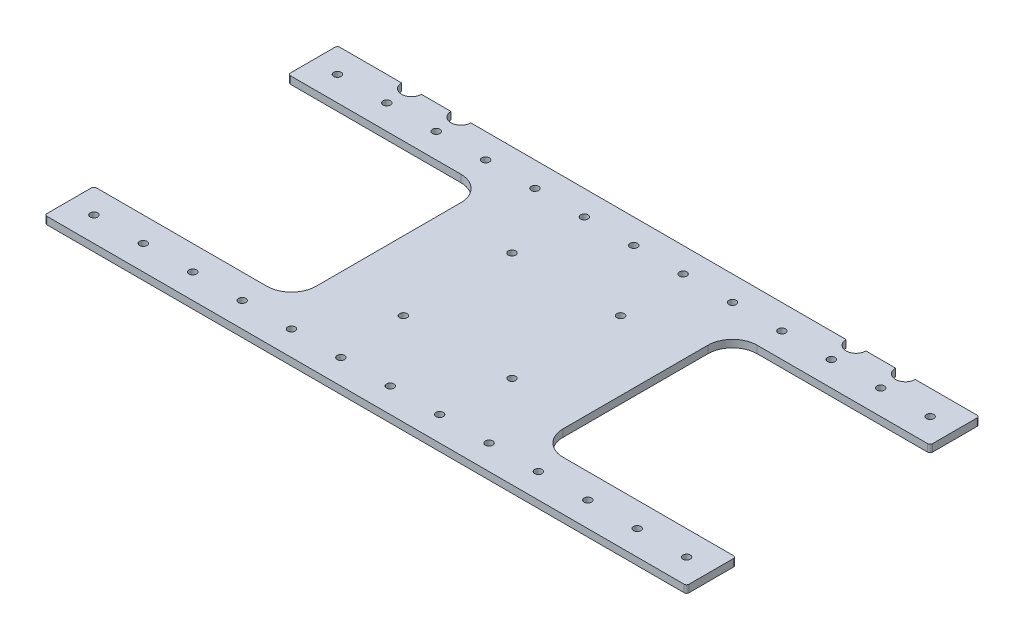
SolidWorks part; units mm, degrees
ref_plane "Front Plane" through (0, 0, 0) normal (0, 0, 1) x (1, 0, 0)
ref_plane "Top Plane" through (0, 0, 0) normal (0, 1, 0) x (1, 0, 0)
ref_plane "Right Plane" through (0, 0, 0) normal (1, 0, 0) x (0, 0, -1)
sketch "草图1" plane through (0, 0, 0) normal (0, 1, 0) x (1, 0, 0)
  line L0 (0, -1387.2) -> (0, -193.6) construction
  line L1 (-50, -193.6) -> (50, -193.6)
  line L2 (-50, -163.6) -> (-50, -105)
  line L3 (-50, 193.6) -> (50, 193.6)
  line L4 (50, -163.6) -> (50, -105)
  line L5 (-130, 193.6) -> (-130, 173.6)
  line L6 (-60, 173.6) -> (-130, 173.6)
  line L7 (50, 193.6) -> (130, 193.6)
  line L9 (60, 173.6) -> (130, 173.6)
  line L10 (130, 193.6) -> (130, 173.6)
  line L11 (-1100, 0) -> (-130, 0) construction
  line L13 (-50, 193.6) -> (-130, 193.6)
  line L14 (-50, -193.6) -> (-130, -193.6)
  line L16 (130, -193.6) -> (130, -173.6)
  line L17 (60, -173.6) -> (130, -173.6)
  line L19 (50, -193.6) -> (130, -193.6)
  line L20 (-60, -173.6) -> (-130, -173.6)
  line L21 (-130, -193.6) -> (-130, -173.6)
  line L22 (-50, -193.6) -> (50, -193.6)
  line L23 (130, 193.6) -> (130, 173.6)
  line L25 (130, 95) -> (130, 75)
  line L28 (60, 95) -> (130, 95)
  line L29 (130, 75) -> (130, 95)
  line L30 (50, 105) -> (50, 163.6)
  line L31 (-130, 75) -> (-130, 95)
  line L32 (-60, 95) -> (-130, 95)
  line L34 (-130, 95) -> (-130, 75)
  line L37 (-130, -95) -> (-130, -75)
  line L39 (-60, -95) -> (-130, -95)
  line L40 (-130, -75) -> (-130, -95)
  line L41 (130, -75) -> (130, -95)
  line L42 (60, -95) -> (130, -95)
  line L44 (130, -95) -> (130, -75)
  line L47 (0, 0) -> (0, 132.8327) construction
  line L49 (-50, 105) -> (-50, 163.6)
  line L50 (130, 75) -> (130, -75)
  line L51 (-130, 75) -> (-130, -75)
  line L52 (130, 0) -> (1130, 0) construction
  arc A0 (60, -173.6) -> (50, -163.6) centre (60, -163.6) cw
  arc A1 (60, -95) -> (50, -105) centre (60, -105) ccw
  arc A2 (-50, -163.6) -> (-60, -173.6) centre (-60, -163.6) cw
  arc A3 (-50, -105) -> (-60, -95) centre (-60, -105) ccw
  arc A7 (50, 105) -> (60, 95) centre (60, 105) ccw
  arc A8 (60, 173.6) -> (50, 163.6) centre (60, 163.6) ccw
  arc A9 (-50, 105) -> (-60, 95) centre (-60, 105) cw
  arc A10 (-50, 163.6) -> (-60, 173.6) centre (-60, 163.6) ccw
  point P0 (0, 0)
  point P43 (50, -173.6)
  point P46 (50, -95)
  point P49 (-50, -173.6)
  point P52 (-50, -95)
  point P64 (50, 95)
  point P67 (50, 173.6)
  point P70 (-50, 95)
  point P73 (-50, 173.6)
  dimension "D8" = 10
  dimension "D1" = 100
  dimension "D2" = 387.2
  dimension "D3" = 20
  dimension "D4" = 80
  dimension "D5" = 118.6
extrude "凸台-拉伸1" add sketch "草图1" along normal blind 3
sketch "草图2" plane through (0, 3, 0) normal (0, 1, 0) x (1, 0, 0)
  line L0 (-130, -95) -> (-130, -75)
  line L1 (-130, -95) -> (-130, 95) construction
  line L3 (-130, -75) -> (185.124, -75)
  line L4 (-130, -75) -> (-130, 215.5703)
  line L5 (-130, 215.5703) -> (185.124, 215.5703)
  line L6 (185.124, -75) -> (185.124, 215.5703)
  arc M1 (-60, 173.6) -> (-50, 163.6) centre (-60, 163.6) cw
  line M2 (-50, 163.6) -> (-50, 105)
  arc M3 (-50, 105) -> (-60, 95) centre (-60, 105) cw
  line M4 (-60, 95) -> (-130, 95)
  line M5 (-130, 95) -> (-130, -95)
  line M19 (130, -95) -> (130, 95)
  line M20 (130, 95) -> (60, 95)
  arc M21 (60, 95) -> (50, 105) centre (60, 105) cw
  line M22 (50, 105) -> (50, 163.6)
  arc M23 (50, 163.6) -> (60, 173.6) centre (60, 163.6) cw
  line M24 (60, 173.6) -> (130, 173.6)
  line M25 (130, 173.6) -> (130, 193.6)
  line M26 (130, 193.6) -> (-130, 193.6)
  line M27 (-130, 193.6) -> (-130, 173.6)
  line M28 (-130, 173.6) -> (-60, 173.6)
  dimension "D1" = 20
extrude "切除-拉伸1" cut sketch "草图2" against normal blind 10 contours L3 M5 M19 M20 M21 M22 M23 M24 M25 M26 M27 M28 M1 M2 M3 M4
sketch "草图3" plane through (0, 3, 0) normal (0, 1, 0) x (1, 0, 0)
  line L0 (130, -75) -> (130, -95) construction
  line L1 (-130, -75) -> (130, -75) construction
  line L2 (-100, -75) -> (-100, -35)
  line L3 (-100, -35) -> (-80, -35)
  line L4 (-80, -35) -> (-80, -75)
  line L5 (-80, -75) -> (-100, -75)
  line L6 (-130, -75) -> (130, -75)
  line L7 (-130, -75) -> (-130, -95)
  line L8 (-130, -95) -> (130, -95)
  line L9 (130, -75) -> (130, -95)
  line L10 (60, -95) -> (130, -95) construction
  line L11 (0, 0) -> (0, -48.7684)
  line L12 (80, -75) -> (100, -75)
  line L13 (80, -35) -> (80, -75)
  line L14 (100, -35) -> (80, -35)
  line L15 (100, -75) -> (100, -35)
  dimension "D2" = 40
  dimension "D3" = 20
extrude "凸台-拉伸2" add sketch "草图3" against normal blind 3 contours L6 L15 L14 L13 | L4 L5 L2 L3
fillet "圆角2" radius 1 6 edges at (-130, 1.5, 193.6) (-130, 1.5, 173.6) (-130, 1.5, 95) (-130, 1.5, 75) (-100, 1.5, 35) (-80, 1.5, 35)
ref_plane "基准面1" through (0, 0, 0) normal (-1, 0, 0) x (0, 0, 1)
fillet "圆角3" radius 1 6 edges at (130, 1.5, 173.6) (130, 1.5, 193.6) (130, 1.5, 95) (130, 1.5, 75) (100, 1.5, 35) (80, 1.5, 35)
sketch "草图4" plane through (0, 3, 0) normal (0, 1, 0) x (1, 0, 0)
  line L1 (-32.5, -164.3) -> (32.5, -164.3)
  line L2 (-32.5, -164.3) -> (-32.5, -104.3)
  line L3 (-32.5, -104.3) -> (32.5, -104.3)
  line L4 (32.5, -164.3) -> (32.5, -104.3)
  line L5 (-32.5, -164.3) -> (32.5, -104.3) construction
  line L6 (-32.5, -104.3) -> (32.5, -164.3) construction
  point P0 (0, -134.3)
  dimension "D1" = 60
  dimension "D2" = 65
sketch "草图5" plane through (0, 3, 0) normal (0, 1, 0) x (1, 0, 0)
  circle A0 centre (22, -112.3) radius 1.5
  circle A1 centre (-22, -112.3) radius 1.5
  circle A2 centre (-22, -156.3) radius 1.5
  circle A3 centre (22, -156.3) radius 1.5
  point P0 (0, -134.3)
  dimension "D2" = 3
  dimension "D3" = 3
  dimension "D4" = 3
  dimension "D5" = 3
  dimension "D1" = 44
extrude "切除-拉伸2" cut sketch "草图5" against normal blind 10
sketch "草图6" plane through (0, 3, 0) normal (0, 1, 0) x (1, 0, 0)
  circle A0 centre (0, -183.6) radius 1.5
  circle A1 centre (-20, -183.6) radius 1.5
  circle A2 centre (-40, -183.6) radius 1.5
  circle A3 centre (-60, -183.6) radius 1.5
  circle A4 centre (-80, -183.6) radius 1.5
  circle A5 centre (-100, -183.6) radius 1.5
  circle A6 centre (-120, -183.6) radius 1.5
  circle A7 centre (0, -183.6) radius 1.5
  circle A8 centre (-20, -183.6) radius 1.5
  circle A9 centre (-40, -183.6) radius 1.5
  circle A10 centre (-60, -183.6) radius 1.5
  circle A11 centre (-80, -183.6) radius 1.5
  circle A12 centre (-100, -183.6) radius 1.5
  circle A13 centre (20, -183.6) radius 1.5
  circle A14 centre (0, -183.6) radius 1.5
  circle A15 centre (-20, -183.6) radius 1.5
  circle A16 centre (-40, -183.6) radius 1.5
  circle A17 centre (-60, -183.6) radius 1.5
  circle A18 centre (-80, -183.6) radius 1.5
  circle A19 centre (40, -183.6) radius 1.5
  circle A20 centre (20, -183.6) radius 1.5
  circle A21 centre (0, -183.6) radius 1.5
  circle A22 centre (-20, -183.6) radius 1.5
  circle A23 centre (-40, -183.6) radius 1.5
  circle A24 centre (-60, -183.6) radius 1.5
  circle A25 centre (60, -183.6) radius 1.5
  circle A26 centre (40, -183.6) radius 1.5
  circle A27 centre (20, -183.6) radius 1.5
  circle A28 centre (0, -183.6) radius 1.5
  circle A29 centre (-20, -183.6) radius 1.5
  circle A30 centre (-40, -183.6) radius 1.5
  circle A31 centre (80, -183.6) radius 1.5
  circle A32 centre (60, -183.6) radius 1.5
  circle A33 centre (40, -183.6) radius 1.5
  circle A34 centre (20, -183.6) radius 1.5
  circle A35 centre (0, -183.6) radius 1.5
  circle A36 centre (-20, -183.6) radius 1.5
  circle A37 centre (100, -183.6) radius 1.5
  circle A38 centre (80, -183.6) radius 1.5
  circle A39 centre (60, -183.6) radius 1.5
  circle A40 centre (40, -183.6) radius 1.5
  circle A41 centre (20, -183.6) radius 1.5
  circle A42 centre (0, -183.6) radius 1.5
  circle A43 centre (20, -183.6) radius 1.5
  circle A44 centre (40, -183.6) radius 1.5
  circle A45 centre (60, -183.6) radius 1.5
  circle A46 centre (80, -183.6) radius 1.5
  circle A47 centre (100, -183.6) radius 1.5
  circle A48 centre (120, -183.6) radius 1.5
  circle A49 centre (120, -85) radius 1.5
  circle A50 centre (100, -85) radius 1.5
  circle A51 centre (80, -85) radius 1.5
  circle A52 centre (60, -85) radius 1.5
  circle A53 centre (40, -85) radius 1.5
  circle A54 centre (20, -85) radius 1.5
  circle A55 centre (0, -85) radius 1.5
  circle A56 centre (20, -85) radius 1.5
  circle A57 centre (40, -85) radius 1.5
  circle A58 centre (60, -85) radius 1.5
  circle A59 centre (80, -85) radius 1.5
  circle A60 centre (100, -85) radius 1.5
  circle A61 centre (-20, -85) radius 1.5
  circle A62 centre (0, -85) radius 1.5
  circle A63 centre (20, -85) radius 1.5
  circle A64 centre (40, -85) radius 1.5
  circle A65 centre (60, -85) radius 1.5
  circle A66 centre (80, -85) radius 1.5
  circle A67 centre (-40, -85) radius 1.5
  circle A68 centre (-20, -85) radius 1.5
  circle A69 centre (0, -85) radius 1.5
  circle A70 centre (20, -85) radius 1.5
  circle A71 centre (40, -85) radius 1.5
  circle A72 centre (60, -85) radius 1.5
  circle A73 centre (-60, -85) radius 1.5
  circle A74 centre (-40, -85) radius 1.5
  circle A75 centre (-20, -85) radius 1.5
  circle A76 centre (0, -85) radius 1.5
  circle A77 centre (20, -85) radius 1.5
  circle A78 centre (40, -85) radius 1.5
  circle A79 centre (-80, -85) radius 1.5
  circle A80 centre (-60, -85) radius 1.5
  circle A81 centre (-40, -85) radius 1.5
  circle A82 centre (-20, -85) radius 1.5
  circle A83 centre (0, -85) radius 1.5
  circle A84 centre (20, -85) radius 1.5
  circle A85 centre (-100, -85) radius 1.5
  circle A86 centre (-80, -85) radius 1.5
  circle A87 centre (-60, -85) radius 1.5
  circle A88 centre (-40, -85) radius 1.5
  circle A89 centre (-20, -85) radius 1.5
  circle A90 centre (0, -85) radius 1.5
  circle A91 centre (-120, -85) radius 1.5
  circle A92 centre (-100, -85) radius 1.5
  circle A93 centre (-80, -85) radius 1.5
  circle A94 centre (-60, -85) radius 1.5
  circle A95 centre (-40, -85) radius 1.5
  circle A96 centre (-20, -85) radius 1.5
  circle A97 centre (0, -85) radius 1.5
  dimension "D1" = 3
  dimension "D2" = 7
  dimension "D3" = 7
extrude "切除-拉伸3" cut sketch "草图6" against normal blind 10 contours A49 | A51 | A50 | A52 | A53 | A54 | A55 | A61 | A67 | A73 | A79 | A85 | A91 | A5 | A6 | A4 | A3 | A2 | A1 | A0 | A13 | A19 | A25 | A31 | A37 | A48
sketch "草图8" plane through (0, 0, 0) normal (0, -1, 0) x (1, 0, 0)
  circle A0 centre (-90, 40) radius 1.5
  circle A1 centre (-90, 60) radius 1.5
  circle A2 centre (90, 60) radius 1.5
  circle A3 centre (90, 40) radius 1.5
  dimension "D1" = 3
  dimension "D2" = 3
extrude "切除-拉伸4" cut sketch "草图8" against normal through all
sketch "草图10" plane through (0, 3, 0) normal (0, 1, 0) x (1, 0, 0)
  circle A0 centre (-100, -75) radius 4
  circle A1 centre (-80, -75) radius 4
  circle A2 centre (80, -75) radius 4
  circle A3 centre (100, -75) radius 4
  dimension "D1" = 8
  dimension "D2" = 8
  dimension "D3" = 8
  dimension "D4" = 8
extrude "切除-拉伸6" cut sketch "草图10" against normal through all
sketch "草图11" plane through (0, 3, 0) normal (0, 1, 0) x (1, 0, 0)
  line L1 (-77.8852, -75) -> (-118.7652, -75)
  line L2 (-77.8852, -75) -> (-77.8852, 75)
  line L3 (-77.8852, 75) -> (-118.7652, 75)
  line L4 (-118.7652, -75) -> (-118.7652, 75)
  line L6 (-129, -75) -> (129, -75) construction
  line L7 (129.0014, 75) -> (-128.9986, 75) construction
  dimension "D1" = 150
  dimension "D2" = 40.88
extrude "切除-拉伸7" cut sketch "草图11" against normal blind 10
sketch "草图12" plane through (0, 3, 0) normal (0, 1, 0) x (1, 0, 0)
  line L0 (104, -75) -> (129, -75) construction
  line L1 (116.5, -75) -> (40.6344, -75)
  line L2 (116.5, -75) -> (116.5, -19.1226)
  line L3 (116.5, -19.1226) -> (40.6344, -19.1226)
  line L4 (40.6344, -75) -> (40.6344, -19.1226)
extrude "切除-拉伸8" cut sketch "草图12" against normal blind 10
